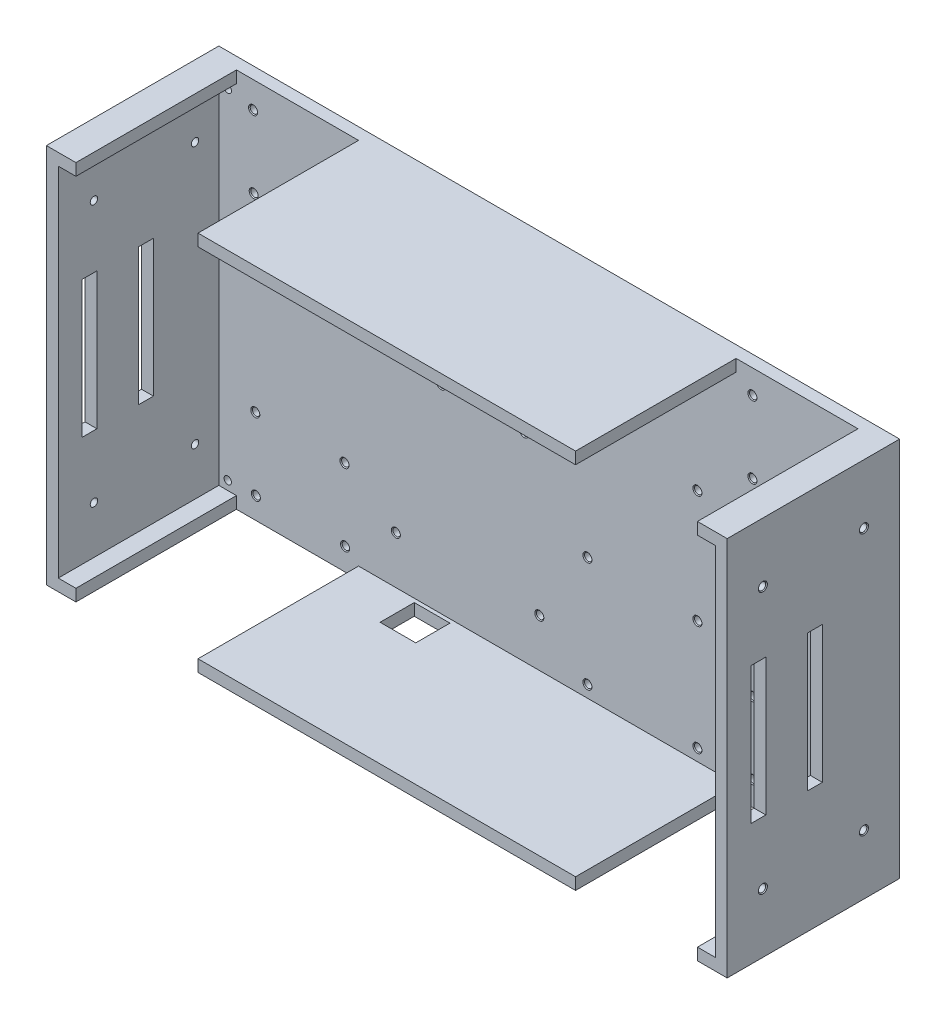
SolidWorks part; units mm, degrees
ref_plane "前视基准面" through (0, 0, 0) normal (0, 0, 1) x (1, 0, 0)
ref_plane "上视基准面" through (0, 0, 0) normal (0, 1, 0) x (1, 0, 0)
ref_plane "右视基准面" through (0, 0, 0) normal (1, 0, 0) x (0, 0, -1)
sketch "底板设计" plane through (0, 0, 0) normal (0, 0, 1) x (1, 0, 0)
  line L0 (-107.7979, 85.0724) -> (-107.7979, -34.9276)
  line L1 (-107.7979, -34.9276) -> (101.2021, -34.9276)
  line L2 (101.2021, -34.9276) -> (101.2021, 85.0724)
  line L3 (101.2021, 85.0724) -> (-107.7979, 85.0724)
  line L11 (60.2021, 85.0724) -> (60.2021, 30.0724)
  line L12 (60.2021, 30.0724) -> (101.2021, 30.0724)
  line L14 (101.2021, 20.0724) -> (60.2021, 20.0724)
  line L15 (60.2021, 20.0724) -> (60.2021, -34.9276)
  line L16 (-66.7979, 85.0724) -> (-66.7979, 30.0724)
  line L17 (-66.7979, 30.0724) -> (-107.7979, 30.0724)
  line L19 (-66.7979, -34.9276) -> (-66.7979, 20.0724)
  line L20 (-66.7979, 20.0724) -> (-107.7979, 20.0724)
  line L22 (-46.639, 32.0151) -> (-12.639, 32.0151)
  line L23 (-46.639, 32.0151) -> (-46.639, -17.9849)
  line L24 (-46.639, -17.9849) -> (-12.639, -17.9849)
  line L25 (-12.639, 32.0151) -> (-12.639, -17.9849)
  line L26 (-20.6883, 85.0724) -> (-5.6883, 85.0724)
  line L27 (50.2021, 8.4047) -> (7.2021, 8.4047)
  line L28 (50.2021, 85.0724) -> (7.2021, 85.0724)
  line L29 (50.2021, 85.0724) -> (50.2021, 42.0724)
  line L30 (50.2021, 42.0724) -> (7.2021, 42.0724)
  line L31 (7.2021, 85.0724) -> (7.2021, 42.0724)
  line L32 (50.2021, 8.4047) -> (50.2021, -34.9276)
  line L33 (50.2021, -34.9276) -> (7.2021, -34.9276)
  line L34 (7.2021, 8.4047) -> (7.2021, -34.9276)
  line L35 (-20.6883, 85.0724) -> (-20.6883, 60.0724)
  line L36 (-56.7979, -34.9276) -> (-56.7979, 35.0724)
  line L37 (-56.7979, -34.9276) -> (-2.7979, -34.9276)
  line L38 (-2.7979, -34.9276) -> (-2.7979, 35.0724)
  line L39 (-56.7979, 35.0724) -> (-2.7979, 35.0724)
  line L40 (-56.7979, 85.0724) -> (-26.7979, 85.0724)
  line L41 (-56.7979, 85.0724) -> (-56.7979, 67.0724)
  line L42 (-56.7979, 67.0724) -> (-26.7979, 67.0724)
  line L43 (-26.7979, 85.0724) -> (-26.7979, 67.0724)
  line L44 (-20.6883, 60.0724) -> (-5.6883, 60.0724)
  line L45 (-5.6883, 85.0724) -> (-5.6883, 60.0724)
  dimension "D1" = 120
  dimension "D2" = 10
  dimension "D3" = 41
  dimension "D4" = 209
  dimension "D5" = 55
  dimension "D6" = 34
  dimension "D7" = 43
  dimension "D8" = 43
  dimension "D9" = 70
  dimension "D10" = 54
  dimension "D11" = 10
  dimension "D12" = 10
  dimension "D13" = 30
  dimension "D14" = 18
  dimension "D15" = 10
  dimension "D16" = 50
  dimension "D17" = 15
  dimension "D18" = 25
sketch "草图4" plane through (0, 0, 0) normal (0, 0, 1) x (1, 0, 0)
  line L0 (-117.7979, 89.0724) -> (-117.7979, -38.9276)
  line L1 (-117.7979, -38.9276) -> (111.2021, -38.9276)
  line L2 (111.2021, -38.9276) -> (111.2021, 89.0724)
  line L3 (111.2021, 89.0724) -> (-117.7979, 89.0724)
  line L4 (-107.7979, -34.9276) -> (101.2021, -34.9276) construction
  line L5 (-107.7979, 85.0724) -> (-107.7979, -34.9276) construction
  line L6 (101.2021, 85.0724) -> (-107.7979, 85.0724) construction
  line L7 (101.2021, -34.9276) -> (101.2021, 85.0724) construction
  dimension "D1" = 4
  dimension "D2" = 10
  dimension "D3" = 4
  dimension "D4" = 10
sketch "草图6" plane through (0, 0, 0) normal (0, 0, 1) x (1, 0, 0)
  line L0 (-113.7979, 85.0724) -> (-113.7979, -34.9276)
  line L1 (-113.7979, -34.9276) -> (107.2021, -34.9276)
  line L2 (107.2021, -34.9276) -> (107.2021, 85.0724)
  line L3 (107.2021, 85.0724) -> (-113.7979, 85.0724)
  line L4 (-117.7979, 89.0724) -> (-117.7979, -38.9276) construction
  line L5 (111.2021, -38.9276) -> (111.2021, 89.0724) construction
  line L6 (111.2021, 89.0724) -> (-117.7979, 89.0724) construction
  line L7 (-117.7979, -38.9276) -> (111.2021, -38.9276) construction
  dimension "D1" = 4
  dimension "D2" = 4
  dimension "D3" = 4
  dimension "D4" = 4
extrude "凸台-拉伸2" add sketch "草图4" along normal blind 58
extrude "切除-拉伸2" cut sketch "草图6" along normal blind 58 from offset 4
sketch "草图7" plane through (-117.7979, 0, 0) normal (-1, 0, 0) x (0, 0, 1)
  line L4 (0, 89.0724) -> (0, -38.9276)
  line L5 (0, -38.9276) -> (58, -38.9276)
  line L6 (58, -38.9276) -> (58, 89.0724)
  line L7 (58, 89.0724) -> (0, 89.0724)
  line L8 (0, 89.0724) -> (0, -38.9276)
  line L9 (0, -38.9276) -> (58, -38.9276)
  line L10 (58, -38.9276) -> (58, 89.0724)
  line L11 (58, 89.0724) -> (0, 89.0724)
  dimension "D1" = 0
sketch "草图9" plane through (-117.7979, 0, 0) normal (-1, 0, 0) x (0, 0, 1)
  line L0 (0, 89.0724) -> (0, -38.9276)
  line L1 (0, -38.9276) -> (58, -38.9276)
  line L2 (58, -38.9276) -> (58, 89.0724)
  line L3 (58, 89.0724) -> (0, 89.0724)
  line L4 (0, 25.0724) -> (58, 25.0724) construction
  line L5 (29, 89.0724) -> (29, -38.9276) construction
  point P12 (12, 69.0724)
  point P13 (46, 69.0724)
  point P14 (46, -18.9276)
  point P15 (12, -18.9276)
  dimension "D1" = 20
  dimension "D2" = 12
hole_wizard "M3 螺纹孔5" positions "草图21" profile "草图22" tap size "M3" standard "GB"
sketch "草图21" plane through (111.2021, 0, 0) normal (1, 0, 0) x (0, 0, -1)
  point P0 (-46, 69.0724)
  point P3 (-12, 69.0724)
  point P6 (-12, -18.9276)
  point P9 (-46, -18.9276)
sketch "草图22" plane through (111.2021, 69.0724, 46) normal (0, 1, 0) x (0, 0, -1)
  line L0 (0, 0) -> (0, 4)
  line L1 (0, 4) -> (1.25, 4)
  line L2 (1.25, 4) -> (1.25, 0.275)
  line L3 (1.25, 0.275) -> (1.525, 0)
  line L5 (1.525, 0) -> (0, 0)
  line L6 (-1.25, 0.275) -> (-1.525, 0) construction
  line L11 (0, -6.35) -> (0, 107.95) construction
  dimension "通孔螺纹孔钻头直径" = 2.5
  dimension "通孔螺纹孔钻头深度" = 4
  dimension "近端锥形沉头孔直径" = 3.05
  dimension "近端锥形沉头孔角度" = 90
cosmetic thread "孔螺蚊线17" parameters "D2"=3
cosmetic thread "孔螺蚊线18" parameters "D2"=3
cosmetic thread "孔螺蚊线19" parameters "D2"=3
cosmetic thread "孔螺蚊线20" parameters "D2"=3
hole_wizard "M3 螺纹孔3" positions "3D草图1" profile "草图16" tap size "M3" standard "GB" end condition up to next
sketch3d "3D草图1"
  point P0 (-117.7979, 69.0724, 12)
  point P3 (-117.7979, 69.0724, 46)
  point P6 (-117.7979, -18.9276, 46)
  point P9 (-117.7979, -18.9276, 12)
sketch "草图16" plane through (-117.7979, 69.0724, 12) normal (0, 1, 0) x (0, 0, 1)
  line L0 (0, 0) -> (0, 4)
  line L1 (0, 4) -> (1.25, 4)
  line L2 (1.25, 4) -> (1.25, 0.275)
  line L3 (1.25, 0.275) -> (1.525, 0)
  line L5 (1.525, 0) -> (0, 0)
  line L6 (-1.25, 0.275) -> (-1.525, 0) construction
  line L11 (0, -6.35) -> (0, 107.95) construction
  dimension "通孔螺纹孔钻头直径" = 2.5
  dimension "通孔螺纹孔钻头深度" = 4
  dimension "近端锥形沉头孔直径" = 3.05
  dimension "近端锥形沉头孔角度" = 90
cosmetic thread "孔螺蚊线21" parameters "D1"=4, "D2"=3.5
cosmetic thread "孔螺蚊线22" parameters "D1"=4, "D2"=3.5
cosmetic thread "孔螺蚊线23" parameters "D1"=4, "D2"=3.5
cosmetic thread "孔螺蚊线24" parameters "D1"=4, "D2"=3.5
sketch "草图18" plane through (111.2021, 0, 0) normal (1, 0, 0) x (0, 0, -1)
  point P0 (-46, 69.0724)
  point P1 (-12, 69.0724)
  point P3 (-12, -18.9276)
  point P5 (-46, -18.9276)
sketch "草图23" plane through (-117.7979, 0, 0) normal (-1, 0, 0) x (0, 0, 1)
  line L0 (58, 25.0724) -> (0, 25.0724) construction
  line L1 (58, -38.9276) -> (58, 89.0724) construction
  line L2 (0, -34.9276) -> (0, 35.0724) construction
  line L3 (45, 48.0724) -> (45, 2.0724)
  line L4 (45, 2.0724) -> (50, 2.0724)
  line L5 (50, 2.0724) -> (50, 48.0724)
  line L6 (50, 48.0724) -> (45, 48.0724)
  dimension "D1" = 5
  dimension "D2" = 46
  dimension "D3" = 8
extrude "切除-拉伸3" cut sketch "草图23" against normal through all
sketch "草图24" plane through (0, -38.9276, 0) normal (0, -1, 0) x (1, 0, 0)
  line L0 (-107.8689, 4) -> (-107.8689, 58)
  line L1 (-66.7979, 0) -> (-107.7979, 0) construction
  line L2 (-117.7979, 58) -> (111.2021, 58) construction
  line L3 (-107.8689, 58) -> (-66.7979, 58)
  line L4 (-66.7979, 58) -> (-66.7979, 4)
  line L5 (60.2021, 0) -> (101.2021, 0) construction
  line L6 (-66.7979, 4) -> (-107.8689, 4)
  line L7 (60.2021, 4) -> (60.2021, 58)
  line L9 (60.2021, 58) -> (101.2021, 58)
  line L10 (101.2021, 58) -> (101.2021, 4)
  line L11 (101.2021, 4) -> (60.2021, 4)
  dimension "D1" = 4
  dimension "D2" = 4
extrude "切除-拉伸4" cut sketch "草图24" against normal through all
sketch "草图25" plane through (0, 0, 4) normal (0, 0, 1) x (1, 0, 0)
  line L0 (-113.7979, 25.0724) -> (107.2021, 25.0724) construction
  line L1 (-113.7979, -34.9276) -> (-113.7979, 85.0724) construction
  line L2 (107.2021, 85.0724) -> (107.2021, -34.9276) construction
  line L3 (-3.2979, 85.0724) -> (-2.7979, -34.9276) construction
  line L4 (101.2021, 85.0724) -> (-107.7979, 85.0724) construction
  line L5 (101.2021, -34.9276) -> (101.2021, 85.0724) construction
  line L6 (107.2021, -34.9276) -> (101.2021, -34.9276) construction
  line L7 (-113.7979, 85.0724) -> (-113.7979, -34.9276) construction
  line L8 (-113.7979, 85.0724) -> (-107.8689, 85.0724) construction
  line L9 (-113.7979, -34.9276) -> (-107.8689, -34.9276) construction
  point P11 (104.2021, 82.0724)
  point P12 (104.2021, -31.9276)
  point P13 (-110.7979, -31.9276)
  point P14 (-110.7979, 82.0724)
  dimension "D1" = 3
  dimension "D2" = 3
  dimension "D3" = 3
  dimension "D4" = 3
  dimension "D5" = 3
  dimension "D6" = 3
hole_wizard "M3 螺纹孔6" positions "草图28" profile "草图29" tap size "M3" standard "GB" end condition up to next
sketch "草图28" plane through (0, 0, 0) normal (0, 0, -1) x (-1, 0, 0)
  point P0 (-104.2021, 82.0724)
  point P3 (-104.2021, -31.9276)
  point P6 (110.7979, -31.9276)
  point P9 (110.7979, 82.0724)
sketch "草图29" plane through (104.2021, 82.0724, 0) normal (1, 0, 0) x (0, 1, 0)
  line L0 (0, 0) -> (0, 4)
  line L1 (0, 4) -> (1.25, 4)
  line L2 (1.25, 4) -> (1.25, 0.275)
  line L3 (1.25, 0.275) -> (1.525, 0)
  line L5 (1.525, 0) -> (0, 0)
  line L6 (-1.25, 0.275) -> (-1.525, 0) construction
  line L11 (0, -6.35) -> (0, 107.95) construction
  dimension "通孔螺纹孔钻头直径" = 2.5
  dimension "通孔螺纹孔钻头深度" = 4
  dimension "近端锥形沉头孔直径" = 3.05
  dimension "近端锥形沉头孔角度" = 90
cosmetic thread "孔螺蚊线25" parameters "D2"=3
cosmetic thread "孔螺蚊线26" parameters "D2"=3
cosmetic thread "孔螺蚊线27" parameters "D2"=3
cosmetic thread "孔螺蚊线28" parameters "D2"=3
sketch "草图31" plane through (0, 0, 4) normal (0, 0, 1) x (1, 0, 0)
  line L0 (-107.7979, -34.9276) -> (101.2021, -34.9276) construction
  line L1 (-56.7979, -34.9276) -> (-56.7979, 35.0724) construction
  point P0 (-54.2579, -18.9276)
  point P1 (-5.9979, -18.9276)
  point P2 (-39.0179, 31.8724)
  point P3 (-11.0779, 31.8724)
  dimension "D1" = 16
  dimension "D2" = 2.54
  dimension "D3" = 16
  dimension "D4" = 50.8
  dimension "D5" = 17.78
  dimension "D6" = 45.72
  dimension "D7" = 50.8
  dimension "D8" = 50.8
hole_wizard "M3 螺纹孔7" positions "草图32" profile "草图33" tap size "M3" standard "GB" end condition up to next
sketch "草图32" plane through (0, 0, 4) normal (0, 0, 1) x (1, 0, 0)
  point P0 (-5.9979, -18.9276)
  point P3 (-11.0779, 31.8724)
  point P6 (-39.0179, 31.8724)
  point P9 (-54.2579, -18.9276)
sketch "草图33" plane through (-5.9979, -18.9276, 4) normal (1, 0, 0) x (0, -1, 0)
  line L0 (0, 0) -> (0, 4)
  line L1 (0, 4) -> (1.25, 4)
  line L2 (1.25, 4) -> (1.25, 0.275)
  line L3 (1.25, 0.275) -> (1.525, 0)
  line L5 (1.525, 0) -> (0, 0)
  line L6 (-1.25, 0.275) -> (-1.525, 0) construction
  line L11 (0, -6.35) -> (0, 107.95) construction
  dimension "通孔螺纹孔钻头直径" = 2.5
  dimension "通孔螺纹孔钻头深度" = 4
  dimension "近端锥形沉头孔直径" = 3.05
  dimension "近端锥形沉头孔角度" = 90
cosmetic thread "孔螺蚊线29" parameters "D2"=3
cosmetic thread "孔螺蚊线30" parameters "D2"=3
cosmetic thread "孔螺蚊线31" parameters "D2"=3
cosmetic thread "孔螺蚊线32" parameters "D2"=3
sketch "草图34" plane through (0, 0, 4) normal (0, 0, 1) x (1, 0, 0)
  line L0 (-107.7979, -34.9276) -> (101.2021, -34.9276) construction
  line L7 (-113.7979, 25.0724) -> (107.2021, 25.0724) construction
  point P0 (10.2021, 6.0724)
  point P1 (10.2021, -30.9276)
  point P2 (47.2021, -30.9276)
  point P3 (47.2021, 6.0724)
  point P6 (10.2021, 44.0724)
  point P7 (47.2021, 44.0724)
  point P8 (47.2021, 81.0724)
  point P9 (10.2021, 81.0724)
  dimension "D1" = 4
  dimension "D2" = 4
  dimension "D3" = 37
  dimension "D4" = 37
  dimension "D5" = 37
  dimension "D6" = 37
hole_wizard "M3 螺纹孔8" positions "草图35" profile "草图36" tap size "M3" standard "GB" end condition up to next
sketch "草图35" plane through (0, 0, 4) normal (0, 0, 1) x (1, 0, 0)
  point P0 (10.2021, 44.0724)
  point P3 (10.2021, 81.0724)
  point P6 (47.2021, 81.0724)
  point P9 (47.2021, 44.0724)
  point P12 (47.2021, 6.0724)
  point P15 (47.2021, -30.9276)
  point P18 (10.2021, -30.9276)
  point P21 (10.2021, 6.0724)
sketch "草图36" plane through (10.2021, 44.0724, 4) normal (1, 0, 0) x (0, -1, 0)
  line L0 (0, 0) -> (0, 4)
  line L1 (0, 4) -> (1.25, 4)
  line L2 (1.25, 4) -> (1.25, 0.275)
  line L3 (1.25, 0.275) -> (1.525, 0)
  line L5 (1.525, 0) -> (0, 0)
  line L6 (-1.25, 0.275) -> (-1.525, 0) construction
  line L11 (0, -6.35) -> (0, 107.95) construction
  dimension "通孔螺纹孔钻头直径" = 2.5
  dimension "通孔螺纹孔钻头深度" = 4
  dimension "近端锥形沉头孔直径" = 3.05
  dimension "近端锥形沉头孔角度" = 90
cosmetic thread "孔螺蚊线33" parameters "D2"=3
cosmetic thread "孔螺蚊线34" parameters "D2"=3
cosmetic thread "孔螺蚊线35" parameters "D2"=3
cosmetic thread "孔螺蚊线36" parameters "D2"=3
cosmetic thread "孔螺蚊线37" parameters "D2"=3
cosmetic thread "孔螺蚊线38" parameters "D2"=3
cosmetic thread "孔螺蚊线39" parameters "D2"=3
cosmetic thread "孔螺蚊线40" parameters "D2"=3
sketch "草图37" plane through (0, 0, 4) normal (0, 0, 1) x (1, 0, 0)
  line L0 (60.2021, 85.0724) -> (101.2021, 85.0724) construction
  line L1 (80.7021, 85.0724) -> (80.7021, -34.9276) construction
  line L2 (-107.7979, -34.9276) -> (101.2021, -34.9276) construction
  line L3 (-113.7979, 25.0724) -> (107.2021, 25.0724) construction
  line L4 (-113.7979, 85.0724) -> (-113.7979, -34.9276) construction
  line L5 (107.2021, -34.9276) -> (107.2021, 85.0724) construction
  line L6 (-107.7979, 85.0724) -> (-66.7979, 85.0724) construction
  line L7 (-87.2979, 85.0724) -> (-87.2979, -34.9276) construction
  line L8 (60.2021, 89.0724) -> (101.2021, 89.0724) construction
  line L9 (-3.2979, 85.0724) -> (-2.7979, -34.9276) construction
  line L10 (101.2021, 85.0724) -> (-107.7979, 85.0724) construction
  point P20 (65.7021, 81.0224)
  point P21 (95.7021, 81.0224)
  point P22 (95.7021, 56.8224)
  point P23 (65.7021, 56.8224)
  point P24 (95.7021, -6.6776)
  point P25 (65.7021, -30.8776)
  point P28 (65.7021, -6.6776)
  point P29 (95.7021, -30.8776)
  point P30 (-102.2607, 80.1976)
  point P31 (-72.2618, 80.4476)
  point P37 (-72.0601, 56.2484)
  point P38 (-102.0591, 55.9984)
  point P39 (-101.5299, -7.4994)
  point P40 (-71.5309, -7.2494)
  point P41 (-71.3293, -31.4485)
  point P42 (-101.3282, -31.6985)
  dimension "D1" = 8.05
  dimension "D2" = 24.2
  dimension "D3" = 30
hole_wizard "M3 螺纹孔9" positions "草图38" profile "草图39" tap size "M3" standard "GB" end condition up to next
sketch "草图38" plane through (0, 0, 4) normal (0, 0, 1) x (1, 0, 0)
  point P0 (-102.2607, 80.1976)
  point P3 (-102.0591, 55.9984)
  point P6 (-72.0601, 56.2484)
  point P9 (-72.2618, 80.4476)
  point P12 (65.7021, 81.0224)
  point P15 (95.7021, 81.0224)
  point P18 (95.7021, 56.8224)
  point P21 (65.7021, 56.8224)
  point P24 (65.7021, -6.6776)
  point P27 (95.7021, -6.6776)
  point P30 (95.7021, -30.8776)
  point P33 (65.7021, -30.8776)
  point P36 (-71.3293, -31.4485)
  point P39 (-71.5309, -7.2494)
  point P42 (-101.5299, -7.4994)
  point P45 (-101.3282, -31.6985)
sketch "草图39" plane through (-102.2607, 80.1976, 4) normal (1, 0, 0) x (0, -1, 0)
  line L0 (0, 0) -> (0, 4)
  line L1 (0, 4) -> (1.25, 4)
  line L2 (1.25, 4) -> (1.25, 0.275)
  line L3 (1.25, 0.275) -> (1.525, 0)
  line L5 (1.525, 0) -> (0, 0)
  line L6 (-1.25, 0.275) -> (-1.525, 0) construction
  line L11 (0, -6.35) -> (0, 107.95) construction
  dimension "通孔螺纹孔钻头直径" = 2.5
  dimension "通孔螺纹孔钻头深度" = 4
  dimension "近端锥形沉头孔直径" = 3.05
  dimension "近端锥形沉头孔角度" = 90
cosmetic thread "孔螺蚊线41" parameters "D2"=3
cosmetic thread "孔螺蚊线42" parameters "D2"=3
cosmetic thread "孔螺蚊线43" parameters "D2"=3
cosmetic thread "孔螺蚊线44" parameters "D2"=3
cosmetic thread "孔螺蚊线45" parameters "D2"=3
cosmetic thread "孔螺蚊线46" parameters "D2"=3
cosmetic thread "孔螺蚊线47" parameters "D2"=3
cosmetic thread "孔螺蚊线48" parameters "D2"=3
cosmetic thread "孔螺蚊线49" parameters "D2"=3
cosmetic thread "孔螺蚊线50" parameters "D2"=3
cosmetic thread "孔螺蚊线51" parameters "D2"=3
cosmetic thread "孔螺蚊线52" parameters "D2"=3
cosmetic thread "孔螺蚊线53" parameters "D2"=3
cosmetic thread "孔螺蚊线54" parameters "D2"=3
cosmetic thread "孔螺蚊线55" parameters "D2"=3
cosmetic thread "孔螺蚊线56" parameters "D2"=3
sketch "草图40" plane through (-117.7979, 0, 0) normal (-1, 0, 0) x (0, 0, 1)
  line L0 (26, 48.0724) -> (26, 2.0724)
  line L1 (26, 2.0724) -> (31, 2.0724)
  line L2 (31, 2.0724) -> (31, 48.0724)
  line L5 (31, 48.0724) -> (26, 48.0724)
  line L6 (45, 48.0724) -> (45, 2.0724) construction
  line L7 (50, 2.0724) -> (50, 48.0724) construction
  line L8 (45, 2.0724) -> (50, 2.0724) construction
  dimension "D1" = 14
extrude "切除-拉伸5" cut sketch "草图40" against normal through all
sketch "草图43" plane through (0, -38.9276, 0) normal (0, -1, 0) x (1, 0, 0)
  line L0 (-56.7979, 0) -> (-56.7979, 31.5089) construction
  line L1 (-56.7979, 0) -> (-26.7979, 0) construction
  line L2 (-66.7979, 4) -> (-21.5841, 4) construction
  line L3 (-113.7979, 4) -> (107.2021, 4) construction
  line L4 (-66.7979, 4) -> (-66.7979, 58) construction
  line L5 (-46.7979, 16.75) -> (-34.7979, 16.75)
  line L6 (-46.7979, 16.75) -> (-46.7979, 5.25)
  line L7 (-46.7979, 5.25) -> (-34.7979, 5.25)
  line L8 (-34.7979, 16.75) -> (-34.7979, 5.25)
  dimension "D1" = 2.5
  dimension "D2" = 20
  dimension "D3" = 12
  dimension "D4" = 11.5
extrude "切除-拉伸8" cut sketch "草图43" against normal blind 10.5
